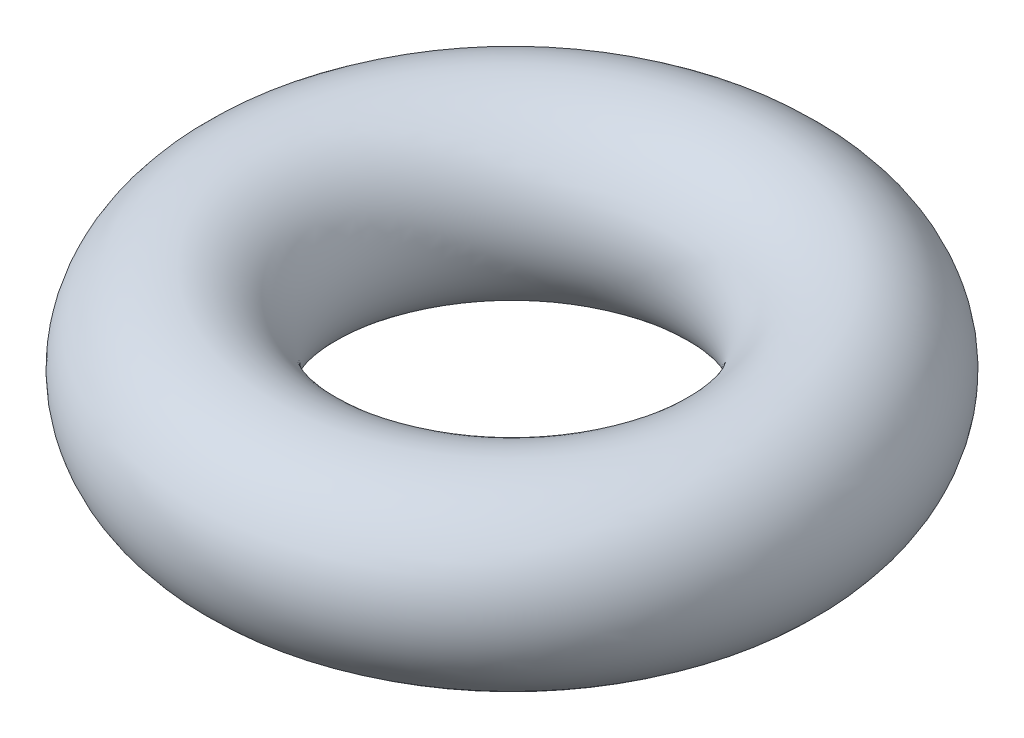
SolidWorks part; units mm, degrees
ref_plane "Front Plane" through (0, 0, 0) normal (0, 0, 1) x (1, 0, 0)
ref_plane "Top Plane" through (0, 0, 0) normal (0, 1, 0) x (1, 0, 0)
ref_plane "Right Plane" through (0, 0, 0) normal (1, 0, 0) x (0, 0, -1)
sketch "Sketch2" plane through (0, 0, 0) normal (0, 0, 1) x (1, 0, 0)
  line L0 (0, 87.4427) -> (0, -78.0227) construction
  circle A0 centre (-50.8, 0) radius 19.05
  dimension "D1" = 38.1
  dimension "D2" = 101.6
revolve "Revolve1" add sketch "Sketch2" angle 360 about L0
